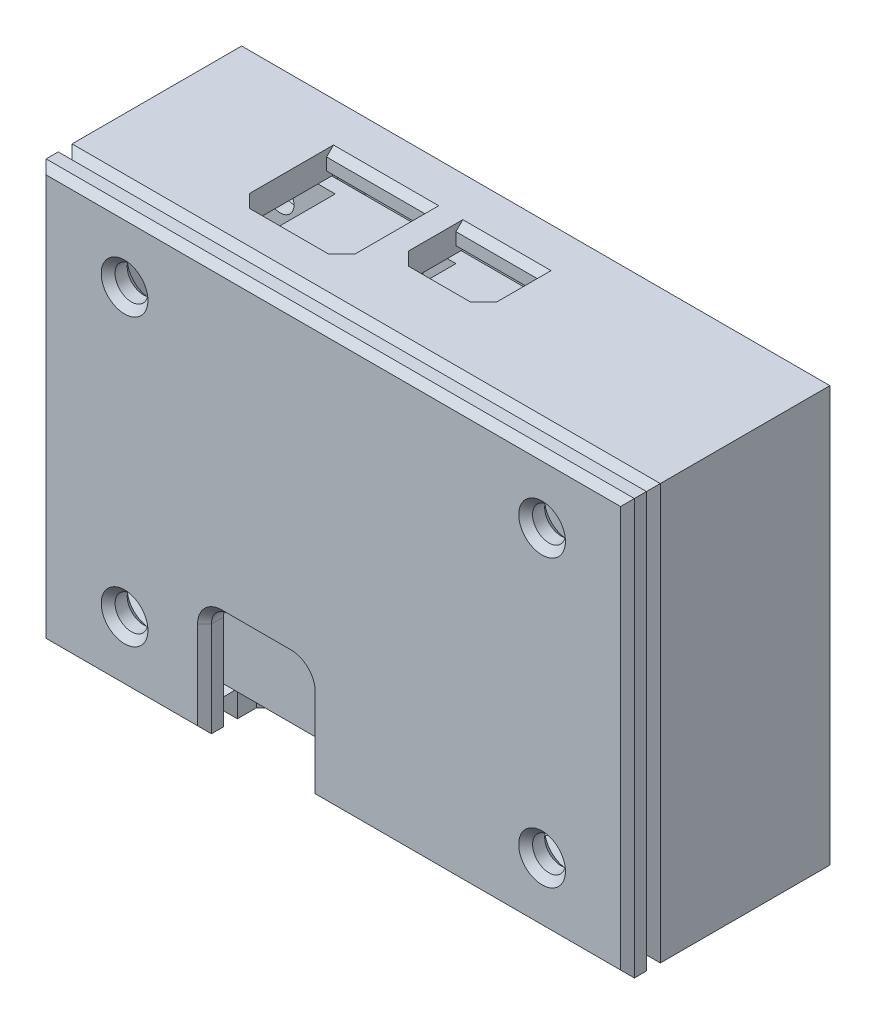
SolidWorks part; units mm, degrees
other "Lid"
other "Box"
other "Circuit"
ref_plane "Front Plane" through (0, 0, 0) normal (0, 0, 1) x (1, 0, 0)
ref_plane "Top Plane" through (0, 0, 0) normal (0, 1, 0) x (1, 0, 0)
ref_plane "Right Plane" through (0, 0, 0) normal (1, 0, 0) x (0, 0, -1)
sketch "Sketch1" plane through (0, 0, 0) normal (0, 0, 1) x (1, 0, 0)
  line L1 (-30, -20) -> (30, -20)
  line L2 (-30, -20) -> (-30, 20)
  line L3 (-30, 20) -> (30, 20)
  line L4 (30, -20) -> (30, 20)
  line L5 (0, 20) -> (0, -20) construction
  line L6 (-30, 0) -> (30, 0) construction
  line L7 (24.13, -16.51) -> (-24.13, -16.51) construction
  line L8 (24.13, -16.51) -> (24.13, 16.51) construction
  line L9 (24.13, 16.51) -> (-24.13, 16.51) construction
  line L10 (-24.13, -16.51) -> (-24.13, 16.51) construction
  line L11 (0, 16.51) -> (0, -16.51) construction
  line L12 (24.13, 0) -> (-24.13, 0) construction
  circle A0 centre (-24.13, 16.51) radius 1.5875
  circle A1 centre (-24.13, -16.51) radius 1.5875
  circle A2 centre (24.13, -16.51) radius 1.5875
  circle A3 centre (24.13, 16.51) radius 1.5875
  point P0 (0, 0)
  point P4 (0, 0)
  dimension "D5" = 3.175
  dimension "D1" = 60
  dimension "D2" = 40
  dimension "D3" = 48.26
  dimension "D4" = 33.02
extrude "Boss-Extrude1" add sketch "Sketch1" along normal blind 1.6
ref_plane "Plane1" through (0, 0, -3) normal (0, 0, -1) x (-1, 0, 0)
sketch "Sketch2" plane through (0, 0, 1.6) normal (0, 0, 1) x (1, 0, 0)
  line L0 (24.13, -16.51) -> (24.13, 16.51) construction
  line L1 (9.47, -5) -> (18.47, -5)
  line L2 (9.47, -5) -> (9.47, -20)
  line L3 (9.47, -20) -> (18.47, -20)
  line L4 (18.47, -5) -> (18.47, -20)
  line L5 (13.97, -20) -> (13.97, -5) construction
  line L6 (9.47, -12.5) -> (18.47, -12.5) construction
  line L7 (-30, -20) -> (30, -20) construction
  point P0 (13.97, -12.5)
  point P8 (0, 0)
  dimension "D1" = 10.16
  dimension "D2" = 9
  dimension "D3" = 15
extrude "Boss-Extrude2" add sketch "Sketch2" along normal blind 11.7
sketch "Sketch3" plane through (0, 0, 1.6) normal (0, 0, 1) x (1, 0, 0)
  line L0 (-24.13, -16.51) -> (-24.13, 16.51) construction
  line L1 (-17.78, 2) -> (0, 2)
  line L2 (-17.78, 2) -> (-17.78, -20)
  line L3 (-17.78, -20) -> (0, -20)
  line L4 (0, 2) -> (0, -20)
  line L5 (-8.89, -20) -> (-8.89, 2) construction
  line L6 (-17.78, -9) -> (0, -9) construction
  line L7 (-30, -20) -> (30, -20) construction
  point P0 (-8.89, -9)
  point P6 (0, 0)
  dimension "D1" = 6.35
  dimension "D2" = 17.78
  dimension "D3" = 22
extrude "Boss-Extrude3" add sketch "Sketch3" along normal blind 15.5
sketch "Sketch4" plane through (0, 0, 1.6) normal (0, 0, 1) x (1, 0, 0)
  line L0 (-30, 20) -> (30, 20) construction
  line L1 (6.37, 12.6) -> (-3.83, 12.6)
  line L2 (6.37, 12.6) -> (6.37, 20)
  line L3 (6.37, 20) -> (-3.83, 20)
  line L4 (-3.83, 12.6) -> (-3.83, 20)
  line L5 (1.27, 20) -> (1.27, 12.6) construction
  line L6 (6.37, 16.3) -> (-3.83, 16.3) construction
  line L7 (24.13, -16.51) -> (24.13, 16.51) construction
  point P0 (1.27, 16.3)
  point P4 (0, 0)
  dimension "D1" = 10.2
  dimension "D2" = 22.86
  dimension "D3" = 7.4
extrude "Boss-Extrude4" add sketch "Sketch4" along normal blind 10.1
sketch "Sketch5" plane through (0, 0, 1.6) normal (0, 0, 1) x (1, 0, 0)
  line L0 (-30, 20) -> (30, 20) construction
  line L1 (-7.62, 20) -> (-17.78, 20)
  line L2 (-7.62, 20) -> (-7.62, 16)
  line L3 (-7.62, 16) -> (-17.78, 16)
  line L4 (-17.78, 20) -> (-17.78, 16)
  line L5 (-12.7, 16) -> (-12.7, 20) construction
  line L6 (-7.62, 18) -> (-17.78, 18) construction
  line L7 (-24.13, -16.51) -> (-24.13, 16.51) construction
  point P0 (-12.7, 18)
  point P4 (0, 0)
  point P7 (0, 0)
  dimension "D1" = 10.16
  dimension "D2" = 11.43
  dimension "D3" = 4
extrude "Boss-Extrude5" add sketch "Sketch5" along normal blind 6.4
sketch "Sketch6" plane through (0, 0, -3) normal (0, 0, -1) x (-1, 0, 0)
  line L0 (20.5425, -20) -> (20.5425, -16.51)
  line L1 (30, -12.9225) -> (24.13, -12.9225)
  line L2 (30, -12.9225) -> (31, -12.9225)
  line L4 (0, 20) -> (0, -20) construction
  line L5 (30, 0) -> (-30, 0) construction
  line L6 (0, 20) -> (0, -20) construction
  line L7 (30, 0) -> (-30, 0) construction
  line L8 (31, -12.9225) -> (31, 0)
  line L9 (20.5425, -20) -> (20.5425, -21)
  line L10 (20.5425, -21) -> (0, -21)
  line L11 (24.13, -16.51) -> (24.13, 16.51) construction
  line L12 (30, -20) -> (30, 20) construction
  line L13 (30, -20) -> (-30, -20) construction
  line L14 (31, -12.9225) -> (34, -12.9225) construction
  line L15 (-34, 24) -> (34, 24)
  line L16 (-34, 24) -> (-34, -24)
  line L17 (-34, -24) -> (34, -24)
  line L18 (34, 24) -> (34, -24)
  line L19 (0, -24) -> (0, 24) construction
  line L20 (-34, 0) -> (34, 0) construction
  line L21 (20.5425, -21) -> (20.5425, -24) construction
  line L22 (31, 12.9225) -> (31, 0)
  line L23 (30, 12.9225) -> (31, 12.9225)
  line L24 (30, 12.9225) -> (24.13, 12.9225)
  line L25 (20.5425, 20) -> (20.5425, 16.51)
  line L26 (20.5425, 20) -> (20.5425, 21)
  line L27 (20.5425, 21) -> (0, 21)
  line L28 (-20.5425, 21) -> (0, 21)
  line L29 (-20.5425, 20) -> (-20.5425, 21)
  line L30 (-20.5425, 20) -> (-20.5425, 16.51)
  line L31 (-30, 12.9225) -> (-24.13, 12.9225)
  line L32 (-30, 12.9225) -> (-31, 12.9225)
  line L33 (-31, 12.9225) -> (-31, 0)
  line L34 (-20.5425, -21) -> (0, -21)
  line L35 (-20.5425, -20) -> (-20.5425, -21)
  line L36 (-31, -12.9225) -> (-31, 0)
  line L37 (-30, -12.9225) -> (-31, -12.9225)
  line L38 (-30, -12.9225) -> (-24.13, -12.9225)
  line L39 (-20.5425, -20) -> (-20.5425, -16.51)
  circle A0 centre (24.13, -16.51) radius 1.35
  circle A1 centre (24.13, 16.51) radius 1.35
  circle A2 centre (-24.13, 16.51) radius 1.35
  circle A3 centre (-24.13, -16.51) radius 1.35
  arc A4 (20.5425, -16.51) -> (24.13, -12.9225) centre (24.13, -16.51) cw
  circle A5 centre (24.13, -16.51) radius 1.5875 construction
  arc A6 (20.5425, 16.51) -> (24.13, 12.9225) centre (24.13, 16.51) ccw
  arc A7 (-20.5425, 16.51) -> (-24.13, 12.9225) centre (-24.13, 16.51) cw
  arc A8 (-20.5425, -16.51) -> (-24.13, -12.9225) centre (-24.13, -16.51) ccw
  circle A9 centre (-24.13, 16.51) radius 1.35
  circle A10 centre (-24.13, -16.51) radius 1.35
  point P14 (24.13, -14.9225)
  point P39 (0, 0)
  point P49 (0, 0)
  point P57 (0, 0)
  point P67 (-24.13, -14.9225)
  point P68 (0, 0)
  dimension "D1" = 2.7
  dimension "D2" = 1
  dimension "D3" = 2
  dimension "D4" = 3
extrude "Boss-Extrude6" add sketch "Sketch6" against normal up to surface (3 mm away) separate body contours L18 L15 L16 L17 A3 A2 A1 A0 L39 A8 L38 L37 L36 L33 L32 L31 A7 L30 L29 L28 L27 L26 L25 A6 L24 L23 L22 L8 L2 L1 A4 L0 L9 L10 L34 L35 up to face at (25.7175, -16.51, 0)
sketch "Sketch7" plane through (0, 0, -3) normal (0, 0, -1) x (-1, 0, 0)
  line L1 (-34, 24) -> (34, 24)
  line L2 (-34, 24) -> (-34, -24)
  line L3 (-34, -24) -> (34, -24)
  line L4 (34, 24) -> (34, -24)
  line L5 (0, -24) -> (0, 24) construction
  line L6 (-34, 0) -> (34, 0) construction
  circle A0 centre (24.13, 16.51) radius 1.35 construction
  circle A1 centre (-24.13, 16.51) radius 1.35 construction
  circle A2 centre (-24.13, -16.51) radius 1.35 construction
  circle A3 centre (24.13, -16.51) radius 1.35 construction
  circle A4 centre (24.13, 16.51) radius 1.35
  circle A5 centre (-24.13, 16.51) radius 1.35
  circle A6 centre (-24.13, -16.51) radius 1.35
  circle A7 centre (24.13, -16.51) radius 1.35
  point P0 (0, 0)
  point P4 (0, 0)
extrude "Boss-Extrude7" add sketch "Sketch7" along normal blind 2
sketch "Sketch8" plane through (0, 0, 0) normal (0, 0, 1) x (1, 0, 0)
  line L0 (34, 24) -> (34, -24) construction
  line L1 (34, -24) -> (-34, -24) construction
  line L2 (-34, 24) -> (-34, -24) construction
  line L3 (34, 24) -> (-34, 24) construction
  line L4 (34, 24) -> (34, -24)
  line L5 (34, -24) -> (-34, -24)
  line L6 (-34, 24) -> (-34, -24)
  line L7 (34, 24) -> (-34, 24)
  line L8 (31, 21) -> (31, -21)
  line L9 (31, -21) -> (-31, -21)
  line L10 (-31, 21) -> (-31, -21)
  line L11 (31, 21) -> (-31, 21)
  point P8 (0, 0)
extrude "Boss-Extrude8" add sketch "Sketch8" along normal offset from surface (16.6 mm away) 15 up to face at (-22.5425, 16.51, 1.6) offset beyond the face yes
sketch "Sketch9" plane through (0, 0, 16.6) normal (0, 0, 1) x (1, 0, 0)
  line L0 (34, 24) -> (34, -24) construction
  line L1 (34, 24) -> (-34, 24) construction
  line L2 (-34, 24) -> (-34, -24) construction
  line L3 (34, -24) -> (-34, -24) construction
  line L4 (34, 24) -> (34, -24)
  line L5 (34, 24) -> (-34, 24)
  line L6 (-34, 24) -> (-34, -24)
  line L7 (34, -24) -> (-34, -24)
  circle A0 centre (-24.13, 16.51) radius 1.9
  circle A1 centre (-24.13, -16.51) radius 1.9
  circle A2 centre (24.13, -16.51) radius 1.9
  circle A3 centre (24.13, 16.51) radius 1.9
  circle A4 centre (-24.13, 16.51) radius 1.5875 construction
  circle A5 centre (-24.13, -16.51) radius 1.5875 construction
  circle A6 centre (24.13, -16.51) radius 1.5875 construction
  circle A7 centre (24.13, 16.51) radius 1.5875 construction
  dimension "D1" = 3.8
extrude "Boss-Extrude9" add sketch "Sketch9" along normal blind 3 separate body
sketch "Sketch10" plane through (0, 0, 19.6) normal (0, 0, 1) x (1, 0, 0)
  line L0 (-8.89, -20) -> (-8.89, 2) construction
  line L1 (-14.89, -24) -> (-2.89, -24)
  line L2 (-14.89, -24) -> (-14.89, -11)
  line L3 (-14.89, -11) -> (-2.89, -11)
  line L4 (-2.89, -24) -> (-2.89, -11)
  line L5 (-8.89, -11) -> (-8.89, -24) construction
  line L6 (-14.89, -17.5) -> (-2.89, -17.5) construction
  line L7 (34, -24) -> (-34, -24) construction
  line L8 (-30, -20) -> (30, -20) construction
  point P0 (-8.89, -17.5)
  point P4 (0, 0)
  point P7 (0, 0)
  dimension "D1" = 12
  dimension "D2" = 9
extrude "Cut-Extrude1" cut sketch "Sketch10" against normal offset from surface (8 mm away) 10 up to face at (-22.5425, 16.51, 1.6)
sketch "Sketch11" plane through (0, -21, 0) normal (0, 1, 0) x (1, 0, 0)
  line L0 (18.97, -13.8) -> (18.97, -3.8)
  line L1 (18.47, -13.3) -> (9.47, -13.3) construction
  line L2 (18.47, -13.3) -> (18.47, -4.3) construction
  line L3 (18.47, -4.3) -> (9.47, -4.3) construction
  line L4 (9.47, -13.3) -> (9.47, -4.3) construction
  line L5 (13.97, -4.3) -> (13.97, -13.3) construction
  line L6 (18.47, -8.8) -> (9.47, -8.8) construction
  line L7 (18.97, -3.8) -> (8.97, -3.8)
  line L8 (8.97, -13.8) -> (8.97, -3.8)
  line L9 (18.97, -13.8) -> (8.97, -13.8)
  point P0 (13.97, -8.8)
  point P4 (0, 0)
  point P5 (0, 0)
  dimension "D1" = 0.5
extrude "Cut-Extrude2" cut sketch "Sketch11" against normal through all
chamfer "Chamfer1" distance 2 angle 45 2 edges at (-2.89, -22.5, 11.6) (-14.89, -22.5, 11.6)
chamfer "Chamfer2" distance 2.5 angle 45 2 edges at (18.97, -22.5, 13.8) (8.97, -22.5, 13.8)
sketch "Sketch12" plane through (0, 21, 0) normal (0, -1, 0) x (1, 0, 0)
  line L0 (30, 1.6) -> (6.37, 1.6) construction
  line L1 (-3.83, 1.6) -> (6.37, 1.6)
  line L2 (-3.83, 1.6) -> (-3.83, 8.6)
  line L3 (-3.83, 8.6) -> (6.37, 8.6)
  line L4 (6.37, 1.6) -> (6.37, 8.6)
  line L5 (1.27, 8.6) -> (1.27, 1.6) construction
  line L6 (-3.83, 5.1) -> (6.37, 5.1) construction
  point P0 (1.27, 5.1)
  point P4 (0, 0)
  dimension "D1" = 7
extrude "Cut-Extrude3" cut sketch "Sketch12" against normal through all
chamfer "Chamfer3" distance 1.5 angle 45 2 edges at (6.37, 22.5, 8.6) (-3.83, 22.5, 8.6)
sketch "Sketch13" plane through (0, 21, 0) normal (0, -1, 0) x (1, 0, 0)
  line L1 (-17.78, 1.6) -> (-7.62, 1.6) construction
  line L2 (-17.78, 1.6) -> (-17.78, 8) construction
  line L3 (-17.78, 8) -> (-7.62, 8) construction
  line L4 (-7.62, 1.6) -> (-7.62, 8) construction
  line L5 (-12.7, 8) -> (-12.7, 1.6) construction
  line L6 (-17.78, 4.8) -> (-7.62, 4.8) construction
  line L7 (-6.62, 1.6) -> (-18.78, 1.6)
  line L8 (-6.62, 1.6) -> (-6.62, 12)
  line L9 (-6.62, 12) -> (-18.78, 12)
  line L10 (-18.78, 1.6) -> (-18.78, 12)
  line L11 (-12.7, 12) -> (-12.7, 1.6) construction
  line L12 (-6.62, 6.8) -> (-18.78, 6.8) construction
  point P0 (-12.7, 4.8)
  point P4 (0, 0)
  point P7 (-12.7, 6.8)
  dimension "D1" = 1
  dimension "D2" = 4
extrude "Cut-Extrude4" cut sketch "Sketch13" against normal through all
chamfer "Chamfer4" distance 1.5 angle 45 2 edges at (-18.78, 22.5, 12) (-6.62, 22.5, 12)
fillet "Fillet1" radius 2 2 edges at (-2.89, -11, 18.1) (-14.89, -11, 18.1)
chamfer "Chamfer5" distance 0.8 angle 45 28 edges at (26.03, 16.51, 19.6) (-22.23, -16.51, 19.6) (-22.23, 16.51, 19.6) (26.03, -16.51, 19.6) (-24.445, -24, 19.6) (-34, 0, 19.6) (0, 24, 19.6) (34, 0, 19.6) (15.555, -24, 19.6) (-2.89, -18.5, 19.6) (-3.4758, -11.5858, 19.6) (-8.89, -11, 19.6) (-14.3042, -11.5858, 19.6) (-14.89, -18.5, 19.6) (26.03, 16.51, 16.6) (26.03, -16.51, 16.6) (-22.23, -16.51, 16.6) (-22.23, 16.51, 16.6) (15.555, -24, 16.6) (34, 0, 16.6) (0, 24, 16.6) (-34, 0, 16.6) (-24.445, -24, 16.6) (-14.89, -18.5, 16.6) (-14.3042, -11.5858, 16.6) (-8.89, -11, 16.6) (-3.4758, -11.5858, 16.6) (-2.89, -18.5, 16.6)
chamfer "Chamfer6" distance 1.2 angle 45 8 edges at (-25.48, -16.51, -5) (22.78, 16.51, -5) (0, -24, -5) (34, 0, -5) (0, 24, -5) (-34, 0, -5) (-25.48, 16.51, -5) (22.78, -16.51, -5)
chamfer "Chamfer7" distance 0.8 angle 45 12 edges at (-34, 0, 16.6) (0, 24, 16.6) (34, 0, 16.6) (15.555, -24, 16.6) (-2.89, -22.5, 16.6) (14.055, -21, 16.6) (31, 0, 16.6) (0, 21, 16.6) (-31, 0, 16.6) (-22.945, -21, 16.6) (-14.89, -22.5, 16.6) (-24.445, -24, 16.6)
chamfer "Chamfer8" distance 0.8 angle 45 8 edges at (1.27, 24, 1.6) (1.27, 21, 1.6) (-12.7, 24, 1.6) (-12.7, 21, 1.6) (13.97, -21, 3.8) (13.97, -24, 3.8) (-8.89, -21, 11.6) (-8.89, -24, 11.6)
chamfer "Chamfer9" distance 0.8 angle 45 16 edges at (27.565, 12.9225, 0) (20.5425, 18.755, 0) (21.5933, 13.9733, 0) (22.78, 16.51, 0) (-27.565, 12.9225, 0) (-20.5425, 18.755, 0) (-21.5933, 13.9733, 0) (-25.48, 16.51, 0) (27.565, -12.9225, 0) (20.5425, -18.755, 0) (21.5933, -13.9733, 0) (22.78, -16.51, 0) (-25.48, -16.51, 0) (-27.565, -12.9225, 0) (-20.5425, -18.755, 0) (-21.5933, -13.9733, 0)
chamfer "Chamfer10" distance 1.6 angle 45 16 edges at (-31, 0, -3) (0, 21, -3) (31, 0, -3) (0, -21, -3) (20.5425, -18.755, -3) (27.565, -12.9225, -3) (21.5933, -13.9733, -3) (-20.5425, 18.755, -3) (-27.565, 12.9225, -3) (-21.5933, 13.9733, -3) (-20.5425, -18.755, -3) (-27.565, -12.9225, -3) (-21.5933, -13.9733, -3) (20.5425, 18.755, -3) (27.565, 12.9225, -3) (21.5933, 13.9733, -3)
